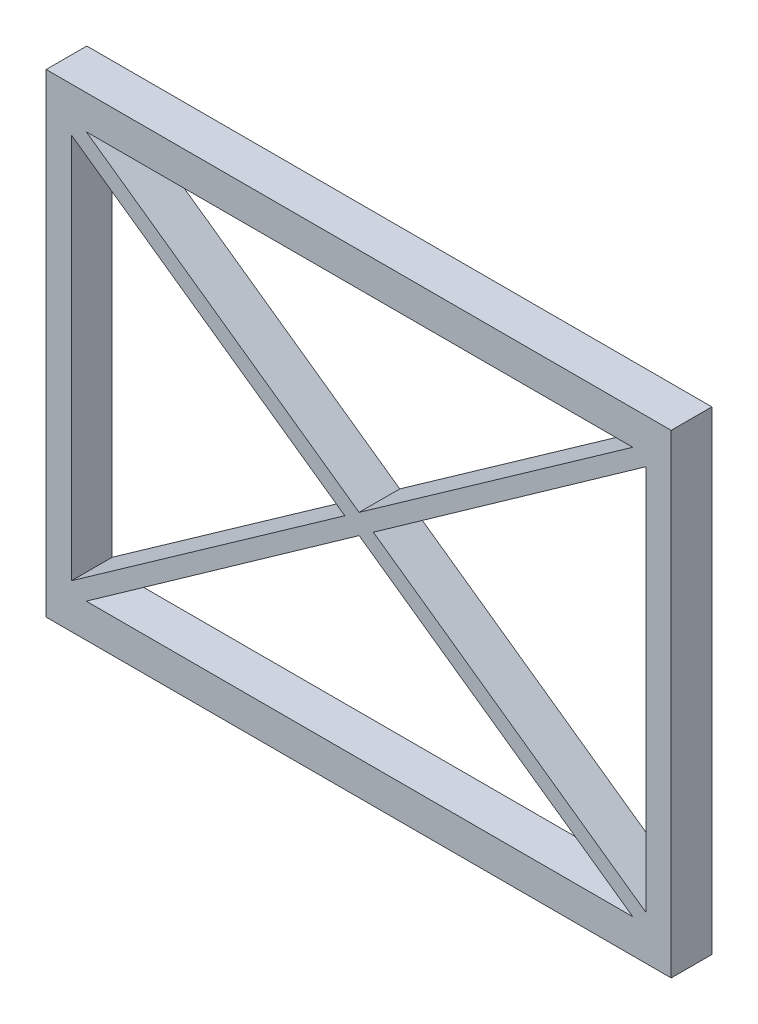
SolidWorks part; units mm, degrees
ref_plane "Front Plane" through (0, 0, 0) normal (0, 0, 1) x (1, 0, 0)
ref_plane "Top Plane" through (0, 0, 0) normal (0, 1, 0) x (1, 0, 0)
ref_plane "Right Plane" through (0, 0, 0) normal (1, 0, 0) x (0, 0, -1)
sketch "Sketch1" plane through (0, 0, 0) normal (0, 1, 0) x (1, 0, 0)
  line L1 (-0.9347, 2.0973) -> (72.8653, 2.0973)
  line L2 (-0.9347, 2.0973) -> (-0.9347, -2.7027)
  line L3 (-0.9347, -2.7027) -> (72.8653, -2.7027)
  line L4 (72.8653, 2.0973) -> (72.8653, -2.7027)
  dimension "D1" = 4.8
  dimension "D2" = 73.8
extrude "Boss-Extrude1" add sketch "Sketch1" along normal blind 56
sketch "Sketch2" plane through (0, 0, 2.7027) normal (0, 0, 1) x (1, 0, 0)
  line L0 (-0.9347, 56) -> (72.8653, 56) construction
  line L1 (2.0653, 52) -> (69.8653, 52)
  line L2 (2.0653, 52) -> (2.0653, 4)
  line L3 (2.0653, 4) -> (69.8653, 4)
  line L4 (69.8653, 52) -> (69.8653, 4)
  line L5 (-0.9347, 0) -> (72.8653, 0) construction
  line L6 (-0.9347, 56) -> (-0.9347, 0) construction
  line L7 (72.8653, 56) -> (72.8653, 0) construction
  line L10 (3.7994, 52) -> (36.0166, 29.1896)
  line L11 (2.0653, 50.776) -> (34.3313, 28)
  line L12 (68.3313, 52) -> (36.0166, 29.1896)
  line L13 (69.8653, 50.776) -> (37.6968, 28)
  line L14 (34.3313, 28) -> (2.0653, 5.224)
  line L16 (36.0166, 26.8104) -> (68.3313, 4)
  line L17 (36.0166, 26.8104) -> (3.7994, 4)
  line L18 (37.6968, 28) -> (69.8653, 5.224)
  dimension "D1" = 4
  dimension "D2" = 4
  dimension "D3" = 3
  dimension "D4" = 3
extrude "Cut-Extrude1" cut sketch "Sketch2" against normal blind 56 contours L12 L1 L10 | L14 L11 L2 | L16 L17 L3 | L13 L18 L4
